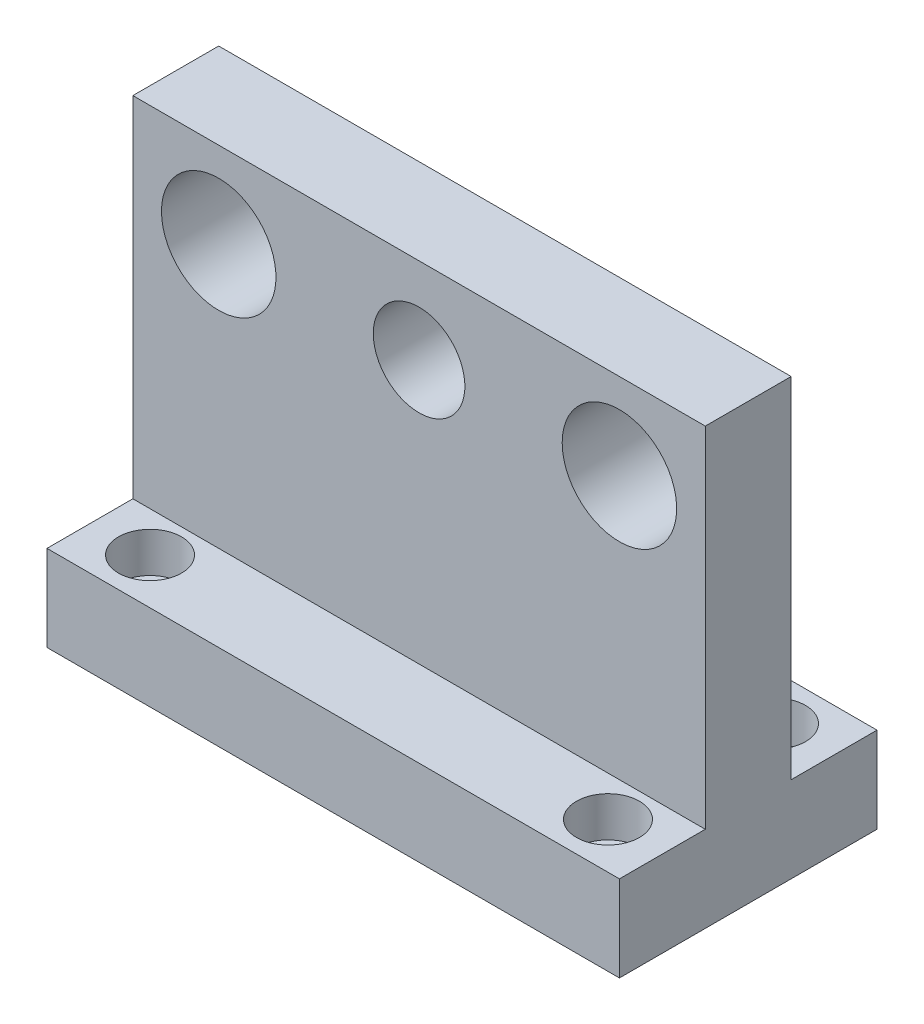
SolidWorks part; units mm, degrees
other "细节项目10"
ref_plane "前视基准面" through (0, 0, 0) normal (0, 0, 1) x (1, 0, 0)
ref_plane "上视基准面" through (0, 0, 0) normal (0, 1, 0) x (1, 0, 0)
ref_plane "右视基准面" through (0, 0, 0) normal (1, 0, 0) x (0, 0, -1)
sketch "草图1" plane through (0, 0, 0) normal (0, 0, 1) x (1, 0, 0)
  line L1 (0, 0) -> (100, 0)
  line L2 (0, 0) -> (0, 61)
  line L3 (0, 61) -> (100, 61)
  line L4 (100, 0) -> (100, 61)
  dimension "D1" = 100
  dimension "D2" = 61
extrude "凸台-拉伸1" add sketch "草图1" along normal blind 15
sketch "草图2" plane through (0, 0, 0) normal (0, -1, 0) x (1, 0, 0)
  line L0 (0, 15) -> (100, 15) construction
  line L1 (0, 30) -> (100, 30)
  line L2 (0, 30) -> (0, -15)
  line L3 (0, -15) -> (100, -15)
  line L4 (100, 30) -> (100, -15)
  dimension "D1" = 45
  dimension "D2" = 15
  dimension "D3" = 100
extrude "凸台-拉伸2" add sketch "草图2" along normal blind 15
sketch "草图3" plane through (0, 0, 0) normal (0, 1, 0) x (1, 0, 0)
  line L0 (0, 15) -> (100, 15) construction
  line L1 (0, 0) -> (0, 15) construction
  line L2 (100, 15) -> (100, 0) construction
  line L3 (-7.6216, -7.5) -> (109.5031, -7.5) construction
  circle A0 centre (10, 7) radius 3.5
  circle A1 centre (90, 7) radius 3.5
  circle A2 centre (90, -22) radius 3.5
  circle A3 centre (10, -22) radius 3.5
  dimension "D1" = 7
  dimension "D2" = 7
  dimension "D3" = 8
  dimension "D4" = 8
  dimension "D5" = 10
  dimension "D6" = 10
extrude "切除-拉伸1" cut sketch "草图3" against normal through all
sketch "草图4" plane through (0, 0, 0) normal (0, 1, 0) x (1, 0, 0)
  circle A0 centre (10, 7) radius 5.5
  circle A1 centre (90, 7) radius 5.5
  circle A2 centre (10, -22) radius 5.5
  circle A3 centre (90, -22) radius 5.5
  dimension "D1" = 11
  dimension "D2" = 11
  dimension "D3" = 11
  dimension "D4" = 11
extrude "切除-拉伸2" cut sketch "草图4" against normal blind 7
sketch "草图5" plane through (0, 0, 0) normal (0, 0, -1) x (-1, 0, 0)
  line L0 (-100, 0) -> (-100, 61) construction
  line L1 (0, 61) -> (0, 0) construction
  line L2 (-100, 61) -> (0, 61) construction
  circle A0 centre (-85, 46) radius 10
  circle A1 centre (-15, 46) radius 10
  circle A2 centre (-50, 46) radius 8
  dimension "D1" = 20
  dimension "D2" = 20
  dimension "D3" = 16
  dimension "D4" = 15
  dimension "D5" = 15
  dimension "D6" = 35
  dimension "D7" = 15
  dimension "D8" = 15
  dimension "D9" = 15
extrude "切除-拉伸3" cut sketch "草图5" against normal through all
cosmetic thread "装饰螺纹线1" parameters "D2"=18
